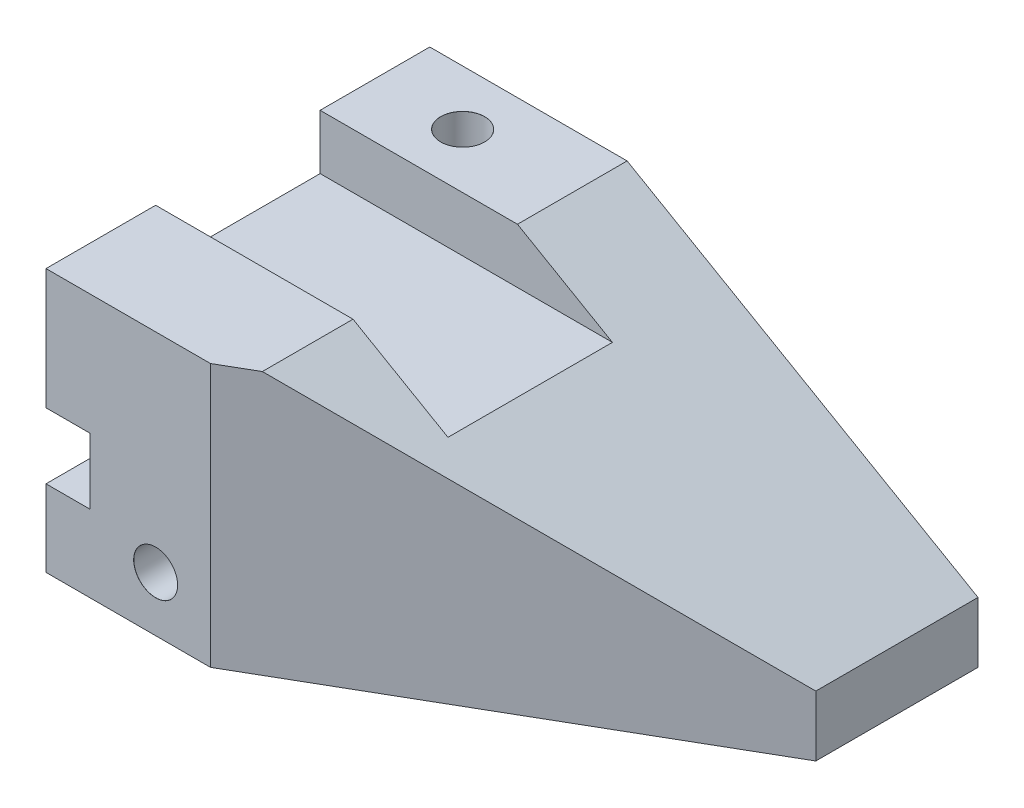
SolidWorks part; units mm, degrees
ref_plane "Front Plane" through (0, 0, 0) normal (0, 0, 1) x (1, 0, 0)
ref_plane "Top Plane" through (0, 0, 0) normal (0, 1, 0) x (1, 0, 0)
ref_plane "Right Plane" through (0, 0, 0) normal (1, 0, 0) x (0, 0, -1)
sketch "Sketch1" plane through (0, 0, 0) normal (0, 1, 0) x (1, 0, 0)
  line L1 (0, 0) -> (250, 0)
  line L2 (0, 0) -> (0, 175)
  line L3 (0, 175) -> (250, 175)
  line L4 (250, 0) -> (250, 175)
  dimension "D1" = 250
  dimension "D2" = 175
extrude "Boss-Extrude1" add sketch "Sketch1" along normal blind 120
sketch "Sketch3" plane through (0, 120, 0) normal (0, 1, 0) x (1, 0, 0)
  line L0 (0, 175) -> (0, 0) construction
  line L1 (0, 125) -> (250, 125)
  line L2 (0, 125) -> (0, 50)
  line L3 (0, 50) -> (250, 50)
  line L4 (250, 125) -> (250, 50)
  line L5 (250, 175) -> (0, 175) construction
  line L6 (0, 0) -> (250, 0) construction
  dimension "D1" = 250
  dimension "5 mm" = 75
  dimension "D2" = 50
  dimension "D3" = 50
extrude "Cut-Extrude1" cut sketch "Sketch3" against normal blind 25
sketch "Sketch4" plane through (0, 0, 0) normal (0, 0, 1) x (1, 0, 0)
  line L0 (0, 120) -> (0, 0) construction
  line L1 (0, 35) -> (20, 35)
  line L2 (0, 35) -> (0, 65)
  line L3 (0, 65) -> (20, 65)
  line L4 (20, 35) -> (20, 65)
  dimension "D1" = 35
  dimension "D2" = 30
  dimension "D3" = 20
extrude "Cut-Extrude2" cut sketch "Sketch4" against normal up to next
hole_wizard "Ø20.0mm Dowel Hole1" positions "Sketch5" profile "Sketch7" hole size "Ø20.0" standard "ANSI Metric" end condition through all
sketch "Sketch5" plane through (0, 0, 0) normal (0, 0, 1) x (1, 0, 0)
  line L0 (0, 0) -> (250, 0) construction
  line L2 (0, 35) -> (0, 0) construction
  point P0 (50, 25)
  point P9 (0, 18.151)
  dimension "D1" = 25
  dimension "D2" = 50
sketch "Sketch7" plane through (50, 25, 0) normal (1, 0, 0) x (0, -1, 0)
  line L0 (0, 0) -> (0, 175)
  line L1 (0, 175) -> (10, 175)
  line L2 (10, 175) -> (10, 0.025)
  line L3 (10, 0.025) -> (10.025, 0)
  line L5 (10.025, 0) -> (0, 0)
  line L6 (-10, 0.025) -> (-10.025, 0) construction
  line L11 (0, -6.35) -> (0, 107.95) construction
  dimension "Thru Hole Dia." = 20
  dimension "Thru Hole Depth" = 175
  dimension "Near C'Sink Dia." = 20.05
  dimension "Near C'Sink Angle" = 90
hole_wizard "Ø20.0mm Dowel Hole2" positions "Sketch8" profile "Sketch9" hole size "Ø20.0" standard "ANSI Metric" end condition through all
sketch "Sketch8" plane through (0, 120, 0) normal (0, 1, 0) x (1, 0, 0)
  line L0 (0, 175) -> (0, 125) construction
  line L1 (250, 175) -> (0, 175) construction
  point P0 (40, 150)
  dimension "D1" = 40
  dimension "D2" = 25
sketch "Sketch9" plane through (40, 120, -150) normal (1, 0, 0) x (0, 0, 1)
  line L0 (0, 0) -> (0, 120)
  line L1 (0, 120) -> (10, 120)
  line L2 (10, 120) -> (10, 0.025)
  line L3 (10, 0.025) -> (10.025, 0)
  line L5 (10.025, 0) -> (0, 0)
  line L6 (-10, 0.025) -> (-10.025, 0) construction
  line L11 (0, -6.35) -> (0, 107.95) construction
  dimension "Thru Hole Dia." = 20
  dimension "Thru Hole Depth" = 120
  dimension "Near C'Sink Dia." = 20.05
  dimension "Near C'Sink Angle" = 90
sketch "Sketch11" plane through (0, 0, 0) normal (0, 0, 1) x (1, 0, 0)
  line L0 (90, 120) -> (250, 27.624)
  line L1 (0, 120) -> (250, 120) construction
  line L2 (250, 120) -> (250, 0) construction
  line L3 (0, 120) -> (0, 65) construction
  line L5 (90, 120) -> (250, 120)
  line L8 (250, 120) -> (250, 27.624)
  dimension "D1" = 30
  dimension "D2" = 90
extrude "Cut-Extrude3" cut sketch "Sketch11" against normal up to next
sketch "Sketch12" plane through (0, 120, 0) normal (0, 1, 0) x (1, 0, 0)
  line L0 (75, 0) -> (250, 101.0363)
  line L1 (90, 0) -> (250, 0) construction
  line L2 (250, 175) -> (250, 0) construction
  line L3 (0, 50) -> (0, 0) construction
  line L5 (75, 0) -> (250, 0)
  line L8 (250, 0) -> (250, 101.0363)
  dimension "D1" = 75
  dimension "D2" = 30
extrude "Cut-Extrude4" cut sketch "Sketch12" against normal up to next
